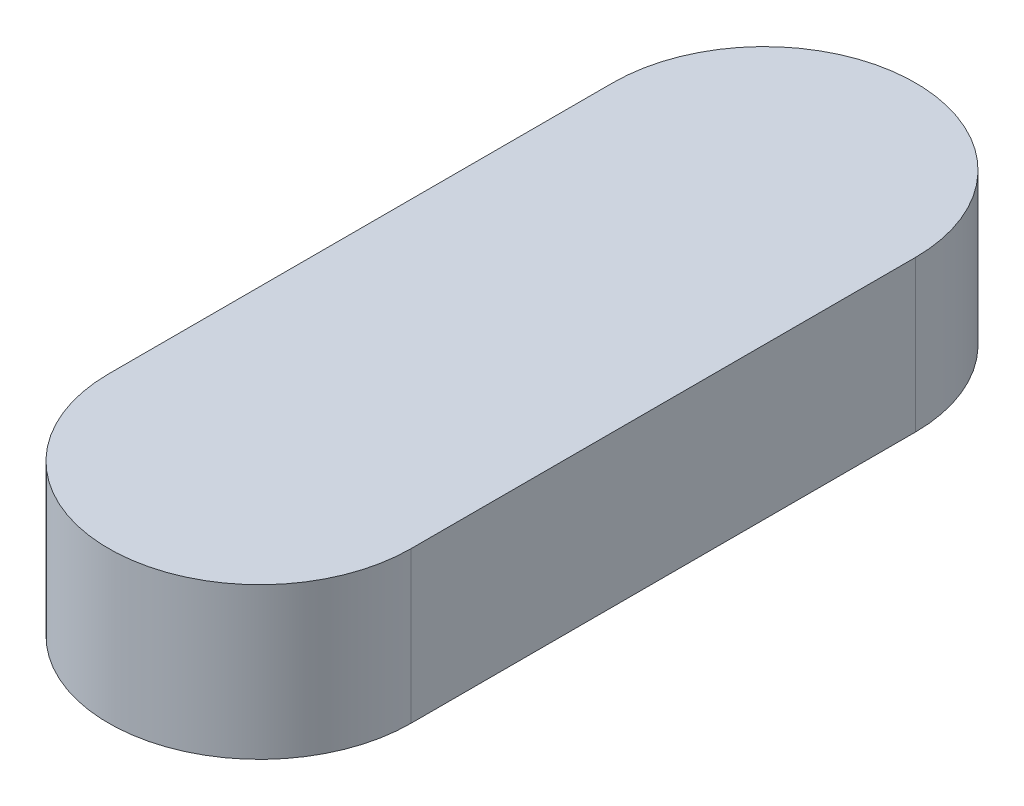
SolidWorks part; units mm, degrees
ref_plane "Alzado" through (0, 0, 0) normal (0, 0, 1) x (1, 0, 0)
ref_plane "Planta" through (0, 0, 0) normal (0, 1, 0) x (1, 0, 0)
ref_plane "Vista lateral" through (0, 0, 0) normal (1, 0, 0) x (0, 0, -1)
sketch "Croquis1" plane through (0, 0, 0) normal (0, 1, 0) x (1, 0, 0)
  line L0 (0, 0) -> (0, 10) construction
  line L1 (-3, 0) -> (-3, 10)
  line L2 (3, 0) -> (3, 10)
  arc A0 (-3, 0) -> (3, 0) centre (0, 0) ccw
  arc A1 (3, 10) -> (-3, 10) centre (0, 10) ccw
  point P3 (0, 5)
  dimension "D2" = 3
  dimension "D1" = 10
extrude "Saliente-Extruir1" add sketch "Croquis1" along normal blind 3
